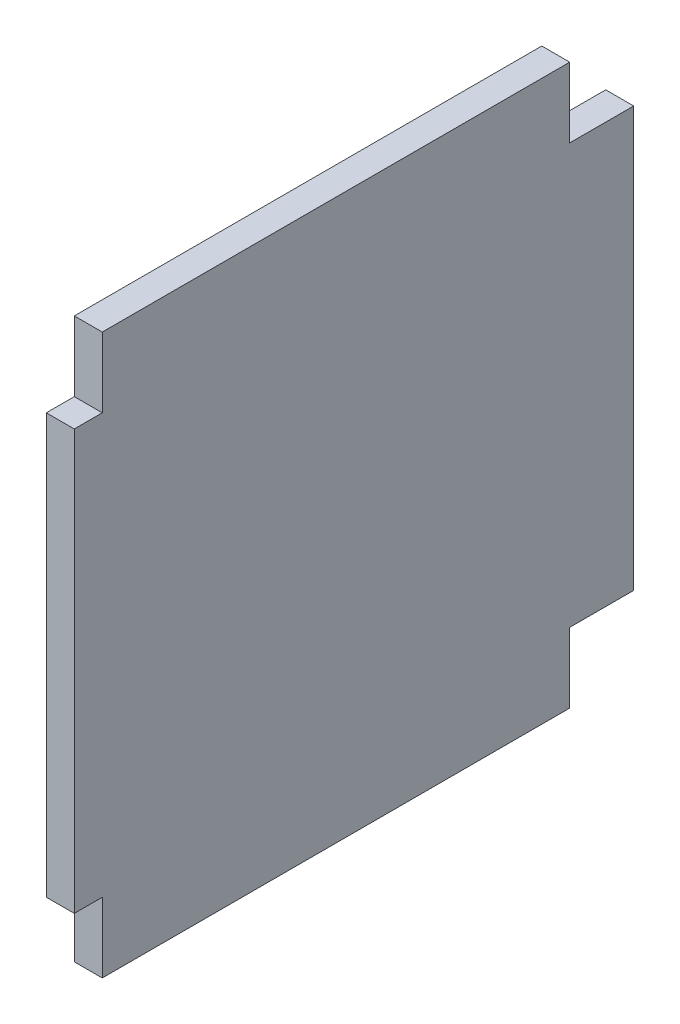
SolidWorks part; units mm, degrees
material "PVC rigido"
ref_plane "Piano frontale" through (0, 0, 0) normal (0, 0, 1) x (1, 0, 0)
ref_plane "Piano superiore" through (0, 0, 0) normal (0, 1, 0) x (1, 0, 0)
ref_plane "Piano destro" through (0, 0, 0) normal (1, 0, 0) x (0, 0, -1)
sketch "Schizzo1" plane through (0, 0, 0) normal (0, 0, 1) x (1, 0, 0)
  line L1 (214, 15) -> (216, 15)
  line L2 (214, 15) -> (214, -15)
  line L3 (214, -15) -> (216, -15)
  line L4 (216, 15) -> (216, -15)
extrude "Estrusione-Estrusione1" add sketch "Schizzo1" along normal up to surface (35.4279 mm away) and the other way up to surface (4.5721 mm away)
ref_plane "Piano1" through (0, 0, 0) normal (0, 1, 0) x (1, 0, 0)
sketch "Schizzo2" plane through (0, -15, 0) normal (0, -1, 0) x (1, 0, 0)
  line L0 (214, 35.4279) -> (214, -4.5721) construction
  line L1 (216, 0) -> (214, 0)
  line L2 (216, 0) -> (216, 33.4279)
  line L3 (216, 33.4279) -> (214, 33.4279)
  line L4 (214, 0) -> (214, 33.4279)
  line L5 (216, 33.4279) -> (214, 33.4279) construction
extrude "Estrusione-Estrusione2" add sketch "Schizzo2" along normal blind 5
mirror "Specchia1" about plane through (0, 0, 0) normal (0, 1, 0) of "Estrusione-Estrusione2"
